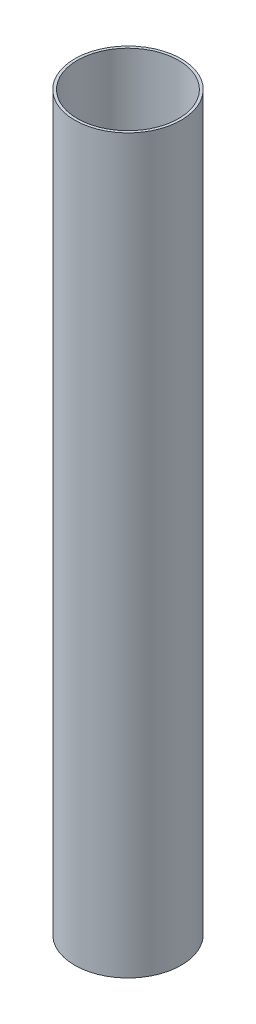
SolidWorks part; units mm, degrees
ref_plane "Front Plane" through (0, 0, 0) normal (0, 0, 1) x (1, 0, 0)
ref_plane "Top Plane" through (0, 0, 0) normal (0, 1, 0) x (1, 0, 0)
ref_plane "Right Plane" through (0, 0, 0) normal (1, 0, 0) x (0, 0, -1)
sketch "Sketch1" plane through (0, 0, 0) normal (0, 1, 0) x (1, 0, 0)
  circle A0 centre (0, 0) radius 38
  circle A1 centre (0, 0) radius 40
  dimension "D1" = 80
  dimension "D2" = 2
extrude "Boss-Extrude1" add sketch "Sketch1" along normal blind 550
